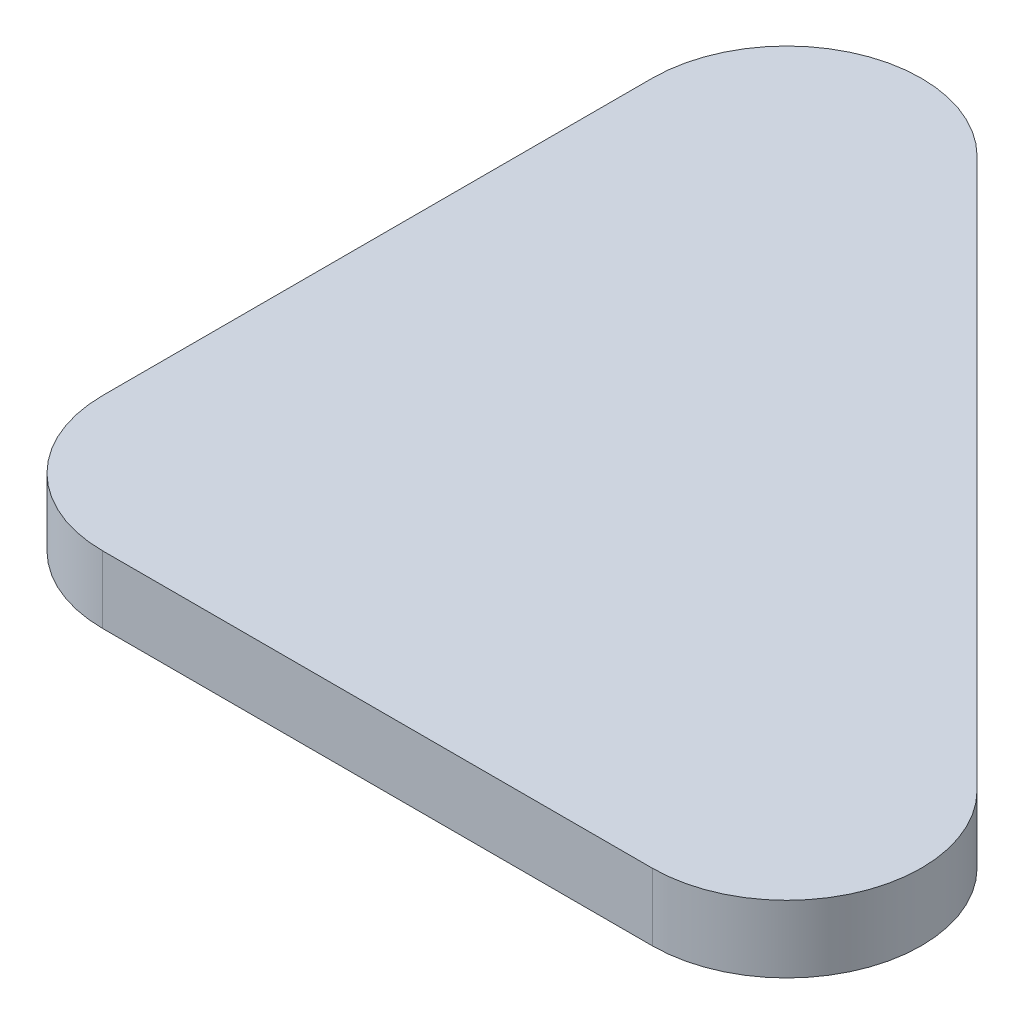
SolidWorks part; units mm, degrees
ref_plane "前视基准面" through (0, 0, 0) normal (0, 0, 1) x (1, 0, 0)
ref_plane "上视基准面" through (0, 0, 0) normal (0, 1, 0) x (1, 0, 0)
ref_plane "右视基准面" through (0, 0, 0) normal (1, 0, 0) x (0, 0, -1)
other "Configuration Table"
sketch "草图1" plane through (0, 0, 0) normal (0, 1, 0) x (1, 0, 0)
  line L0 (0, 0) -> (60, 0)
  line L1 (60, 0) -> (0, 60)
  line L2 (0, 60) -> (0, 0)
  dimension "D1" = 60
  dimension "D2" = 60
extrude "凸台-拉伸1" add sketch "草图1" along normal blind 4
fillet "圆角1" radius 8 3 edges at (0, 2, -60) (0, 2, 0) (60, 2, 0)
